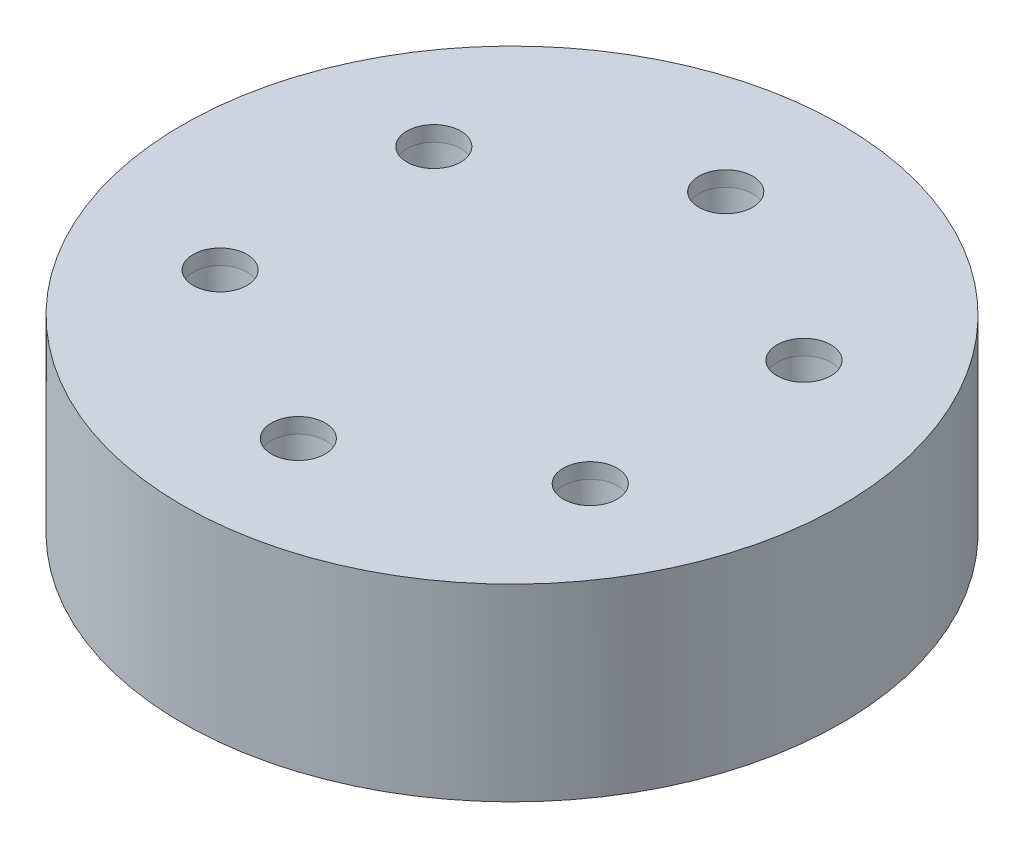
SolidWorks part; units mm, degrees
ref_plane "Alzado" through (0, 0, 0) normal (0, 0, 1) x (1, 0, 0)
ref_plane "Planta" through (0, 0, 0) normal (0, 1, 0) x (1, 0, 0)
ref_plane "Vista lateral" through (0, 0, 0) normal (1, 0, 0) x (0, 0, -1)
sketch "Sketch1" plane through (0, 0, 0) normal (0, 1, 0) x (1, 0, 0)
  circle A0 centre (0, 0) radius 31.7
  dimension "D1" = 63.4
sketch "Sketch2" plane through (0, 0, 0) normal (0, 1, 0) x (1, 0, 0)
  circle A0 centre (0, 0) radius 36.7
  circle A1 centre (0, 0) radius 31.7 construction
  dimension "D1" = 5
extrude "Boss-Extrude1" add sketch "Sketch2" along normal blind 11 contours A0
sketch "Sketch3" plane through (0, 0, 0) normal (1, 0, 0) x (0, 0, -1)
  line L0 (0, 11) -> (0, 0) construction
  line L1 (36.7, 11) -> (-36.7, 11) construction
  line L2 (23.8, 11) -> (23.8, 0) construction
  line L3 (31.7, 0) -> (-31.7, 0) construction
  line L4 (26.8, 11) -> (26.8, 9.3)
  line L5 (26.8, 9.3) -> (25.9, 0.5)
  line L6 (25.9, 0.5) -> (25.9, 0)
  line L7 (25.9, 0) -> (23.8, 0)
  line L8 (23.8, 0) -> (23.8, 11)
  line L9 (23.8, 11) -> (26.8, 11)
  dimension "D1" = 23.8
  dimension "D2" = 6
  dimension "D3" = 4.2
  dimension "D4" = 8.8
  dimension "D5" = 0.5
revolve "Cut-Revolve1" cut sketch "Sketch3" angle 360 about L8
sketch "Sketch5" plane through (0, 0, 0) normal (0, -1, 0) x (1, 0, 0)
  circle A0 centre (0, 0) radius 14.1
  dimension "D1" = 28.2
extrude "Cut-Extrude1" cut sketch "Sketch5" against normal blind 4.5
sketch "Sketch7" plane through (0, 0, 0) normal (0, -1, 0) x (1, 0, 0)
  circle A0 centre (0, 0) radius 36.7
  circle A1 centre (0, 0) radius 31.7
  circle A2 centre (0, 0) radius 31.7 construction
  circle A3 centre (0, 0) radius 36.7 construction
extrude "Boss-Extrude2" add sketch "Sketch7" along normal blind 10
pattern_circular "CirPattern1" count 6 over 360 about axis through (0, 0, 0) along (0, 1, 0) of "Cut-Revolve1"
